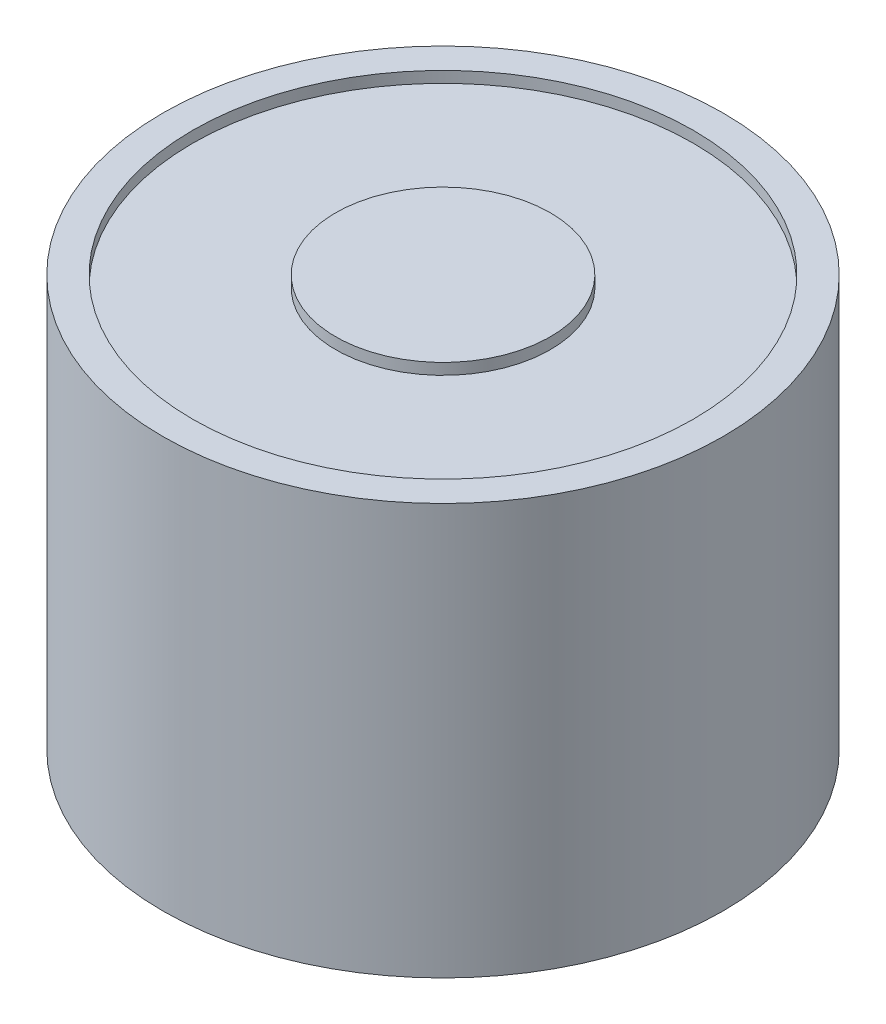
SolidWorks part; units mm, degrees
ref_plane "Front Plane" through (0, 0, 0) normal (0, 0, 1) x (1, 0, 0)
ref_plane "Top Plane" through (0, 0, 0) normal (0, 1, 0) x (1, 0, 0)
ref_plane "Right Plane" through (0, 0, 0) normal (1, 0, 0) x (0, 0, -1)
sketch "Sketch1" plane through (0, 0, 0) normal (0, 0, 1) x (1, 0, 0)
  line L0 (0, 6) -> (0, 22)
  line L1 (0, 22) -> (5.75, 22)
  line L2 (5.75, 22) -> (5.75, 21.4)
  line L3 (5.75, 21.4) -> (13.4, 21.4)
  line L4 (13.4, 21.4) -> (13.4, 22)
  line L5 (13.4, 22) -> (15, 22)
  line L6 (15, 22) -> (15, 0)
  line L7 (15, 0) -> (2, 0)
  line L8 (2, 0) -> (2, 6)
  line L9 (2, 6) -> (0, 6)
  line L10 (0, -2.8269) -> (0, 11.6346) construction
  point P12 (2.5, 22.0028)
  point P14 (3.8053, 21.4)
  dimension "D1" = 4
  dimension "D2" = 6
  dimension "D3" = 22
  dimension "D4" = 0.6
  dimension "D5" = 30
  dimension "D6" = 11.5
  dimension "D7" = 1.6
revolve "Revolve1" add sketch "Sketch1" angle 360 about L10
